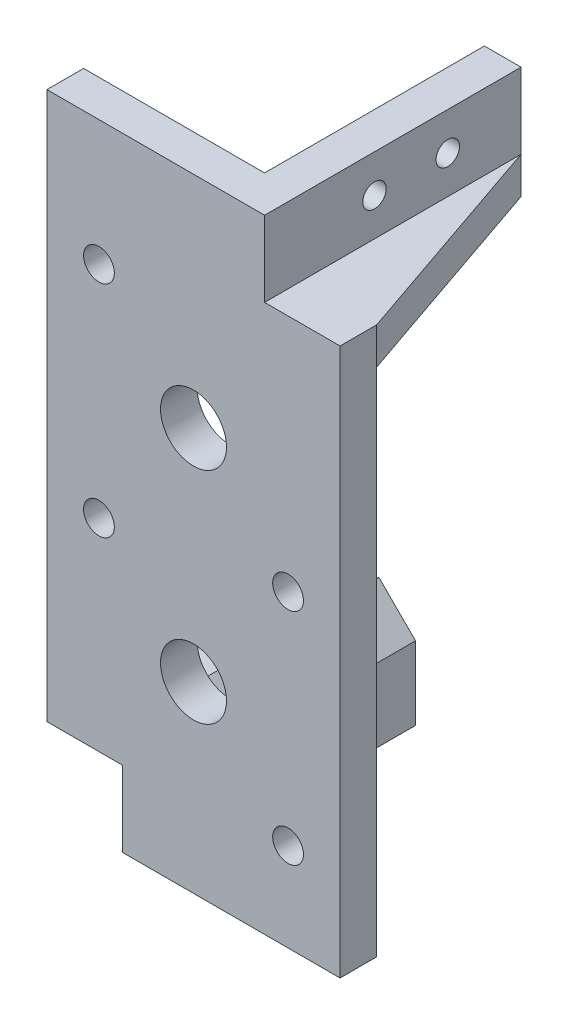
SolidWorks part; units mm, degrees
ref_plane "正面" through (0, 0, 0) normal (0, 0, 1) x (1, 0, 0)
ref_plane "平面" through (0, 0, 0) normal (0, 1, 0) x (1, 0, 0)
ref_plane "右側面" through (0, 0, 0) normal (1, 0, 0) x (0, 0, -1)
sketch "Sketch1" plane through (0, 0, 0) normal (0, 0, 1) x (1, 0, 0)
  line L1 (-40, 42.5) -> (40, 42.5)
  line L2 (-40, 42.5) -> (-40, -42.5)
  line L3 (-40, -42.5) -> (40, -42.5)
  line L4 (40, 42.5) -> (40, -42.5)
  line L5 (-40, 42.5) -> (40, -42.5) construction
  line L6 (-40, -42.5) -> (40, 42.5) construction
  point P0 (0, 0)
  dimension "D1" = 85
  dimension "D2" = 80
extrude "Boss-Extrude1" add sketch "Sketch1" along normal blind 5
sketch "Sketch2" plane through (0, 0, 0) normal (0, 0, -1) x (-1, 0, 0)
  line L0 (-40, 12.5) -> (40, 12.5) construction
  line L1 (-40, -42.5) -> (-40, 42.5) construction
  line L2 (40, 42.5) -> (40, -42.5) construction
  line L3 (-40, 42.5) -> (40, 42.5) construction
  line L4 (0, 42.5) -> (0, -42.5) construction
  line L5 (40, -42.5) -> (-40, -42.5) construction
  line L6 (-7.0953, 25.4047) -> (-32.9047, -0.4047) construction
  circle A0 centre (-20, 12.5) radius 4.5
  circle A2 centre (-7.0953, 25.4047) radius 2.1
  circle A3 centre (-32.9047, -0.4047) radius 2.1
  circle A6 centre (-20, -17.5) radius 4.5
  circle A7 centre (-7.0953, -4.5953) radius 2.1
  circle A8 centre (-32.9047, -30.4047) radius 2.1
  point P18 (-20, 12.5)
  point P21 (-15, -17.5)
  dimension "D4" = 9
  dimension "D8" = 4.2
  dimension "D1" = 30
  dimension "D2" = 20
  dimension "D6" = 36.5
  dimension "D7" = 45
  dimension "D10" = 2
extrude "Cut-Extrude1" cut sketch "Sketch2" against normal up to next
sketch "Sketch3" plane through (0, 0, 0) normal (0, 0, -1) x (-1, 0, 0)
  line L0 (-40, 42.5) -> (40, 42.5) construction
  line L1 (-40, 42.5) -> (-29.7, 42.5)
  line L2 (-40, 42.5) -> (-40, 32.2)
  line L3 (-40, 32.2) -> (-29.7, 32.2)
  line L4 (-29.7, 42.5) -> (-29.7, 32.2)
  line L5 (40, 42.5) -> (30, 42.5)
  line L6 (40, 42.5) -> (40, 32.5)
  line L7 (40, 32.5) -> (30, 32.5)
  line L8 (30, 42.5) -> (30, 32.5)
  line L9 (40, 42.5) -> (40, -42.5) construction
  point P11 (40, 37.5)
  dimension "D1" = 10.3
  dimension "D2" = 10.3
  dimension "D3" = 10
  dimension "D4" = 10
extrude "Cut-Extrude2" cut sketch "Sketch3" against normal up to next
sketch "Sketch4" plane through (0, 0, 0) normal (0, 0, -1) x (-1, 0, 0)
  line L0 (-29.7, 42.5) -> (30, 42.5) construction
  line L1 (40, -42.5) -> (0, -42.5)
  line L2 (40, -42.5) -> (40, 42.5)
  line L3 (40, 42.5) -> (0, 42.5)
  line L4 (0, -42.5) -> (0, 42.5)
  dimension "D1" = 40
extrude "Cut-Extrude4" cut sketch "Sketch4" against normal blind 10
sketch "Sketch5" plane through (0, 0, 0) normal (0, 0, -1) x (-1, 0, 0)
  line L1 (-29.7, 42.5) -> (-24.7, 42.5)
  line L2 (-29.7, 42.5) -> (-29.7, 32.2)
  line L3 (-29.7, 32.2) -> (-24.7, 32.2)
  line L4 (-24.7, 42.5) -> (-24.7, 32.2)
  dimension "D1" = 10.3
  dimension "D2" = 5
extrude "Boss-Extrude2" add sketch "Sketch5" along normal blind 30
sketch "Sketch6" plane through (0, 32.2, 0) normal (0, -1, 0) x (1, 0, 0)
  line L0 (40, 0) -> (29.7, -30)
  line L1 (29.7, -30) -> (24.7, -30)
  line L2 (24.7, -30) -> (24.7, 5)
  line L3 (0, 5) -> (40, 5) construction
  line L4 (24.7, 5) -> (40, 5)
  line L5 (40, 5) -> (40, 0)
extrude "Boss-Extrude3" add sketch "Sketch6" along normal blind 5
sketch "Sketch7" plane through (0, 0, 0) normal (0, 0, -1) x (-1, 0, 0)
  line L1 (0, -42.5) -> (-10.3, -42.5)
  line L2 (0, -42.5) -> (0, -32.2)
  line L3 (0, -32.2) -> (-10.3, -32.2)
  line L4 (-10.3, -42.5) -> (-10.3, -32.2)
  dimension "D1" = 10.3
  dimension "D2" = 10.3
extrude "Cut-Extrude5" cut sketch "Sketch7" against normal up to next
sketch "Sketch8" plane through (0, 0, 0) normal (0, 0, -1) x (-1, 0, 0)
  line L1 (-10.3, -42.5) -> (-15.3, -42.5)
  line L2 (-10.3, -42.5) -> (-10.3, -27.5)
  line L3 (-10.3, -27.5) -> (-15.3, -27.5)
  line L4 (-15.3, -42.5) -> (-15.3, -27.5)
  dimension "D1" = 5
  dimension "D2" = 15
extrude "Boss-Extrude4" add sketch "Sketch8" along normal blind 30
sketch "Sketch9" plane through (0, -27.5, 0) normal (0, 1, 0) x (1, 0, 0)
  line L0 (10.3, 30) -> (0, 0)
  line L1 (0, 0) -> (10.3, 0)
  line L2 (24.7, 0) -> (0, 0) construction
  line L3 (10.3, 30) -> (10.3, 0) construction
  line L4 (10.3, 0) -> (10.3, 30)
extrude "Boss-Extrude5" add sketch "Sketch9" against normal blind 5
chamfer "Chamfer1" distance 5 angle 45 1 edges at (15.3, -27.5, -15)
sketch "Sketch10" plane through (10.3, 0, 0) normal (-1, 0, 0) x (0, 0, 1)
  line L0 (-30, -37.5) -> (5, -37.35) construction
  line L1 (-30, -42.5) -> (-30, -32.5) construction
  line L2 (5, -32.2) -> (5, -42.5) construction
  circle A0 centre (-20, -37.4571) radius 1.6
  circle A1 centre (-10, -37.4143) radius 1.6
  dimension "D3" = 3.2
  dimension "D1" = 10
  dimension "D2" = 10
extrude "Cut-Extrude6" cut sketch "Sketch10" against normal up to next
sketch "Sketch12" plane through (29.7, 0, 0) normal (1, 0, 0) x (0, 0, -1)
  line L0 (-5, 37.35) -> (30, 37.35) construction
  line L1 (-5, 32.2) -> (-5, 42.5) construction
  line L2 (30, 42.5) -> (30, 32.2) construction
  circle A0 centre (20, 37.35) radius 1.6
  circle A1 centre (10, 37.35) radius 1.6
  dimension "D1" = 3.2
  dimension "D2" = 10
  dimension "D3" = 10
extrude "Cut-Extrude7" cut sketch "Sketch12" against normal up to next
